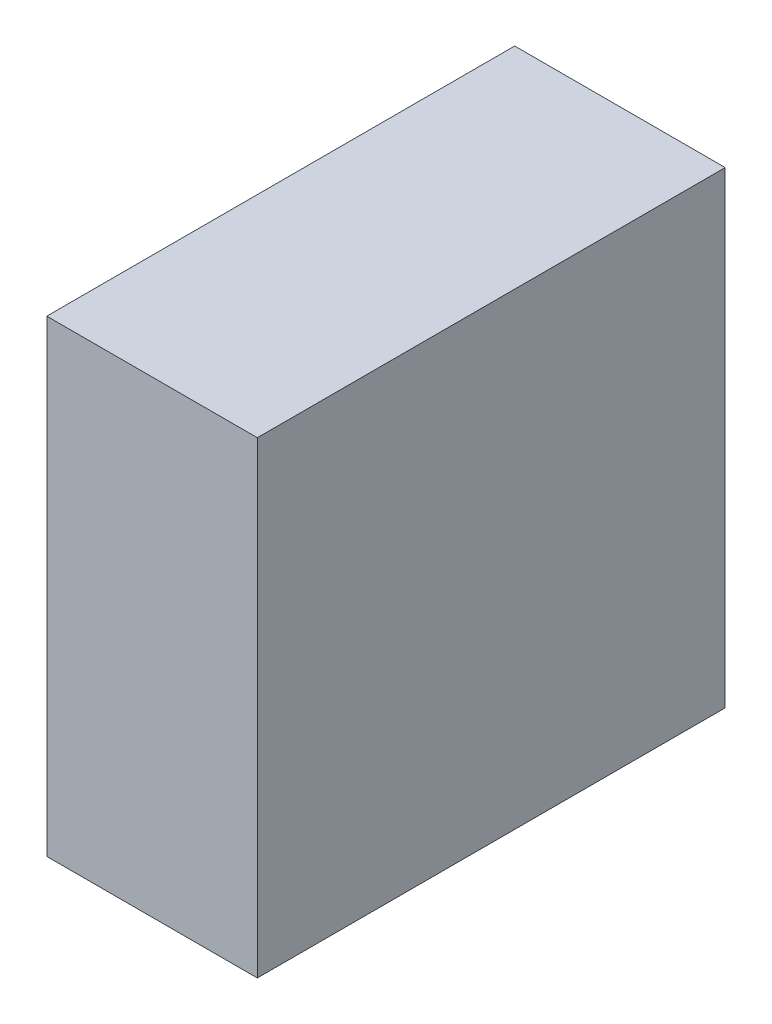
SolidWorks part; units mm, degrees
ref_plane "Front Plane" through (0, 0, 0) normal (0, 0, 1) x (1, 0, 0)
ref_plane "Top Plane" through (0, 0, 0) normal (0, 1, 0) x (1, 0, 0)
ref_plane "Right Plane" through (0, 0, 0) normal (1, 0, 0) x (0, 0, -1)
other "Configuration Table"
sketch "Sketch1" plane through (0, 0, 0) normal (0, 0, 1) x (1, 0, 0)
  line L1 (450, 180) -> (495, 180)
  line L2 (450, 180) -> (450, 280)
  line L3 (450, 280) -> (495, 280)
  line L4 (495, 180) -> (495, 280)
extrude "PACK_pano_motor_surucu_2_1" add sketch "Sketch1" against normal blind 100 from offset 148 separate body
